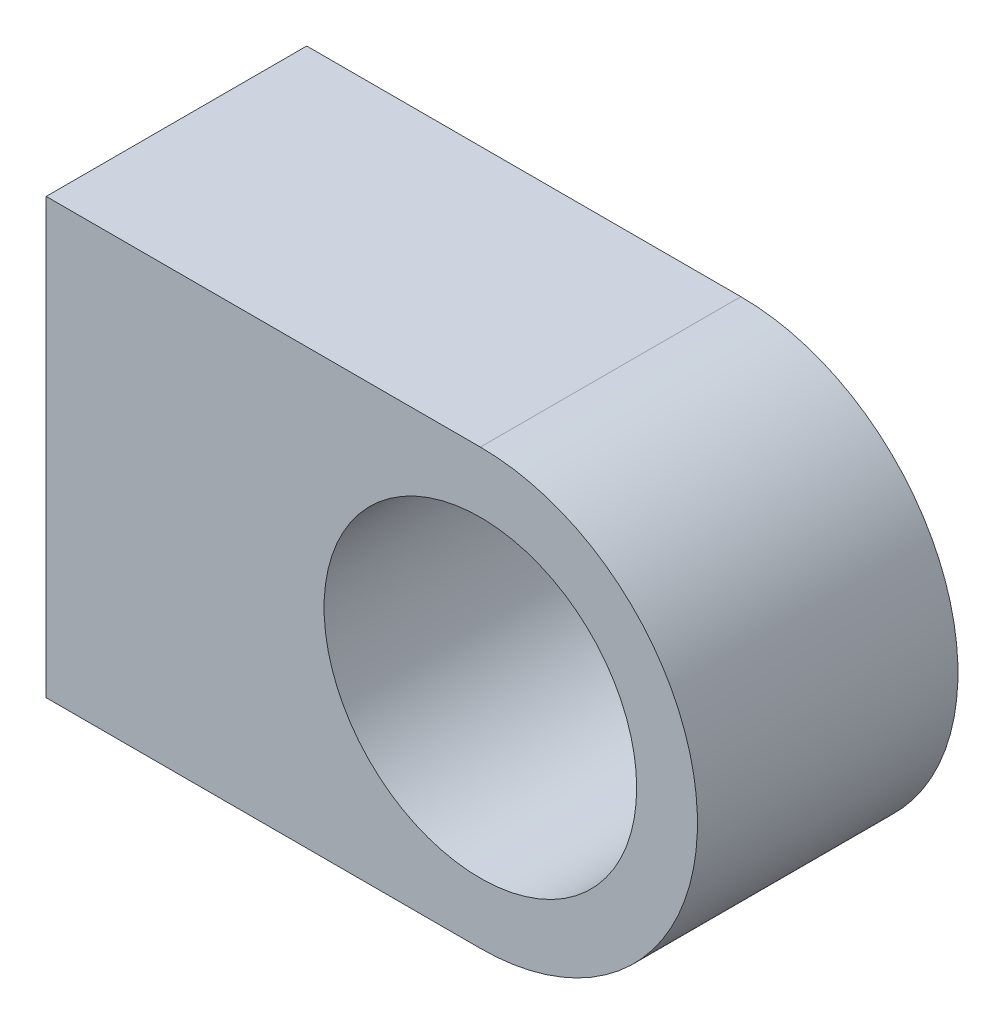
SolidWorks part; units mm, degrees
ref_plane "前视基准面" through (0, 0, 0) normal (0, 0, 1) x (1, 0, 0)
ref_plane "上视基准面" through (0, 0, 0) normal (0, 1, 0) x (1, 0, 0)
ref_plane "右视基准面" through (0, 0, 0) normal (1, 0, 0) x (0, 0, -1)
other "Configuration Table"
sketch "草图2" plane through (0, 0, 0) normal (0, 0, 1) x (1, 0, 0)
  line L0 (0, 0) -> (-5, 0)
  line L1 (-5, 0) -> (-5, -5)
  line L2 (-5, -5) -> (0, -5)
  arc A0 (0, 0) -> (0, -5) centre (0, -2.5) cw
  circle A1 centre (0, -2.5) radius 1.8
extrude "凸台-拉伸1" add sketch "草图2" along normal blind 3
